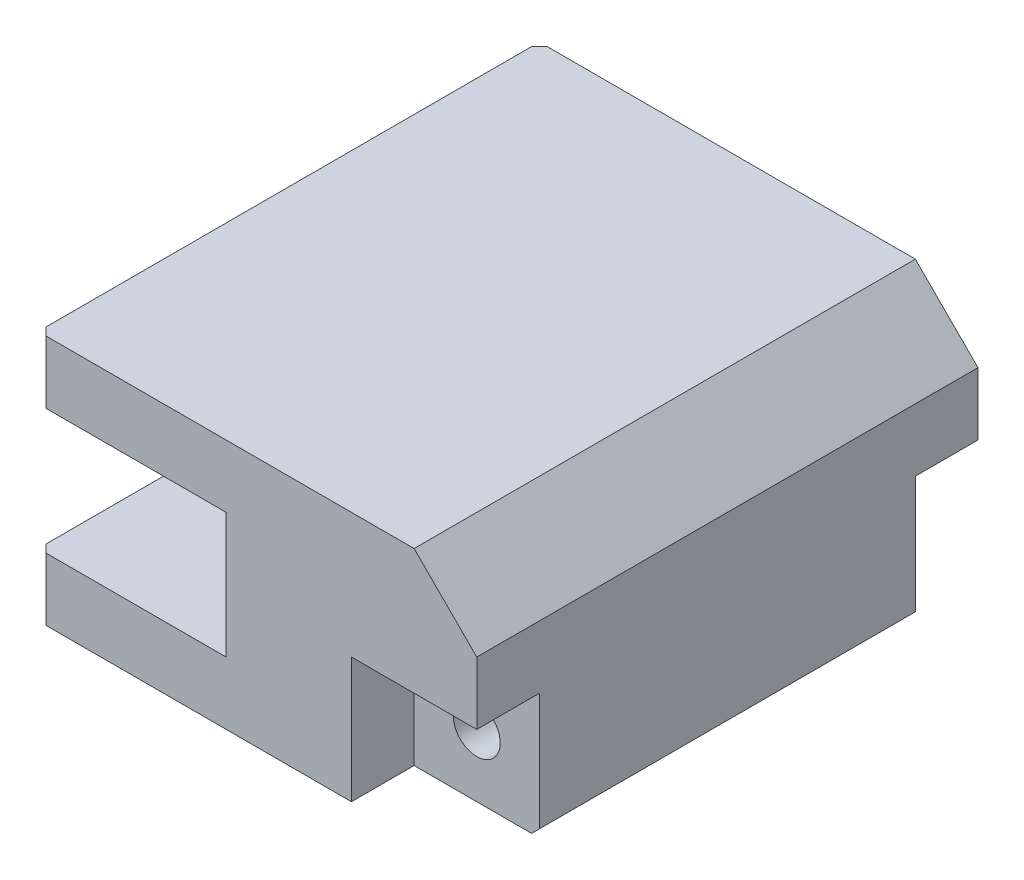
SolidWorks part; units mm, degrees
material "6061-T6 (SS)"
ref_plane "Front Plane" through (0, 0, 0) normal (0, 0, 1) x (1, 0, 0)
ref_plane "Top Plane" through (0, 0, 0) normal (0, 1, 0) x (1, 0, 0)
ref_plane "Right Plane" through (0, 0, 0) normal (1, 0, 0) x (0, 0, -1)
sketch "Sketch1" plane through (0, 0, 0) normal (0, 0, 1) x (1, 0, 0)
  line L1 (44.45, -25.4) -> (-44.45, -25.4)
  line L2 (44.45, -25.4) -> (44.45, 25.4)
  line L3 (44.45, 25.4) -> (-44.45, 25.4)
  line L4 (-44.45, -25.4) -> (-44.45, 25.4)
  line L5 (44.45, -25.4) -> (-44.45, 25.4) construction
  line L6 (44.45, 25.4) -> (-44.45, -25.4) construction
  point P0 (0, 0)
  dimension "D1" = 88.9
  dimension "D2" = 50.8
extrude "Boss-Extrude1" add sketch "Sketch1" along normal mid plane 101.6
sketch "Sketch2" plane through (0, 0, 50.8) normal (0, 0, 1) x (1, 0, 0)
  line L2 (44.45, -25.4) -> (19.05, -25.4)
  line L4 (44.45, -25.4) -> (44.45, 0)
  line L5 (44.45, 0) -> (19.05, 0)
  line L6 (19.05, -25.4) -> (19.05, 0)
  dimension "D1" = 25.4
  dimension "D2" = 25.4
extrude "Cut-Extrude1" cut sketch "Sketch2" against normal blind 12.7
sketch "Sketch3" plane through (0, 0, 38.1) normal (0, 0, 1) x (1, 0, 0)
  line L0 (31.75, 0) -> (31.75, -12.7) construction
  line L1 (44.45, 0) -> (19.05, 0) construction
  line L2 (31.75, -12.7) -> (19.05, -12.7) construction
  line L3 (19.05, 0) -> (19.05, -25.4) construction
  circle A0 centre (31.75, -12.7) radius 4.7625
  dimension "D1" = 9.525
  dimension "D2" = 12.7
extrude "Cut-Extrude2" cut sketch "Sketch3" against normal through all
mirror "Mirror1" about plane through (0, 0, 0) normal (0, 0, 1) of "Cut-Extrude1"
sketch "Sketch4" plane through (0, 0, 50.8) normal (0, 0, 1) x (1, 0, 0)
  line L0 (-44.45, 25.4) -> (-44.45, -25.4) construction
  line L1 (-44.45, 12.7) -> (-6.35, 12.7)
  line L2 (-44.45, 12.7) -> (-44.45, -12.7)
  line L3 (-44.45, -12.7) -> (-6.35, -12.7)
  line L4 (-6.35, 12.7) -> (-6.35, -12.7)
  line L5 (-6.35, 0) -> (0, 0) construction
  dimension "D1" = 25.4
  dimension "D2" = 38.1
extrude "Cut-Extrude3" cut sketch "Sketch4" against normal through all
chamfer "Chamfer1" distance 12.7 angle 45 1 edges at (44.45, 25.4, 0)
chamfer "Chamfer2" distance 1.5875 angle 45 5 edges at (-44.45, -19.05, 50.8) (-44.45, -19.05, -50.8) (-44.45, 19.05, -50.8) (-44.45, 19.05, 50.8) (44.45, -25.4, 0)
